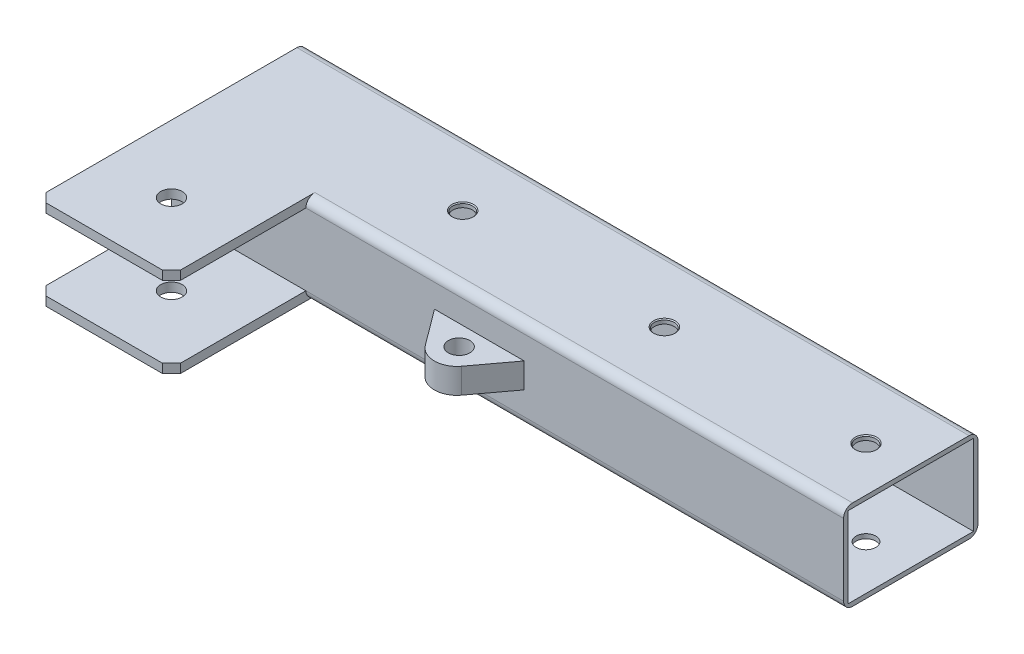
SolidWorks part; units mm, degrees
ref_plane "Front Plane" through (0, 0, 0) normal (0, 0, 1) x (1, 0, 0)
ref_plane "Top Plane" through (0, 0, 0) normal (0, 1, 0) x (1, 0, 0)
ref_plane "Right Plane" through (0, 0, 0) normal (1, 0, 0) x (0, 0, -1)
sketch "Sketch1" plane through (0, 0, 0) normal (0, 1, 0) x (1, 0, 0)
  line L3 (-375, 75) -> (375, 75)
  line L4 (375, -75) -> (375, 75)
  line L5 (-375, -75) -> (375, 75) construction
  line L6 (-375, 75) -> (375, -75) construction
  line L8 (-225, -75) -> (375, -75)
  line L11 (-375, 75) -> (-375, -75)
  line L14 (-375, -75) -> (-375, -225)
  line L15 (-375, -225) -> (-225, -225)
  line L16 (-225, -75) -> (-225, -225)
  circle A1 centre (-300, -150) radius 12
  point P0 (0, 0)
  point P6 (-375, -150)
  point P13 (-300, -225)
  dimension "D3" = 150
  dimension "D6" = 24
  dimension "D1" = 750
  dimension "D2" = 150
  dimension "D4" = 150
  dimension "D5" = 150
extrude "Boss-Extrude1" add sketch "Sketch1" along normal blind 100
sketch "Sketch2" plane through (375, 0, 0) normal (1, 0, 0) x (0, 0, -1)
  line L0 (-75, 100) -> (-75, 0) construction
  line L1 (-75, 100) -> (75, 100) construction
  line L2 (-70, 5) -> (70, 5)
  line L3 (75, 100) -> (75, 0) construction
  line L4 (-70, 5) -> (-70, 95)
  line L5 (-70, 95) -> (70, 95)
  line L6 (70, 5) -> (70, 95)
  line L7 (-70, 5) -> (70, 95) construction
  line L8 (-70, 95) -> (70, 5) construction
  point P0 (0, 50)
  point P4 (75, 50)
  dimension "D2" = 5
  dimension "D3" = 5
extrude "Cut-Extrude1" cut sketch "Sketch2" against normal through all contours L2 L6 L5 L4
sketch "Sketch3" plane through (0, 0, 0) normal (-1, 0, 0) x (0, 0, 1)
  line L5 (225, 100) -> (225, 0) construction
  line L6 (375, 10) -> (225, 10)
  line L7 (375, 10) -> (375, 90)
  line L12 (375, 90) -> (225, 90)
  line L14 (272.5, -25) -> (327.5, -25)
  line L15 (375, 10) -> (225, 90) construction
  line L16 (375, 90) -> (225, 10) construction
  line L17 (-75, 100) -> (-75, 0) construction
  line L19 (272.5, 125) -> (327.5, 125)
  line L20 (327.5, -25) -> (327.5, 125)
  line L21 (272.5, -25) -> (327.5, 125) construction
  line L22 (272.5, 125) -> (327.5, -25) construction
  line L24 (225, 10) -> (75, 10)
  line L25 (225, 10) -> (225, 90)
  line L26 (225, 90) -> (75, 90)
  line L27 (75, 90) -> (75, 10)
  point P0 (300, 50)
  point P10 (-75, 50)
  point P11 (300, 50)
  dimension "D1" = 80
  dimension "D2" = 150
  dimension "D3" = 55
  dimension "D4" = 150
extrude "Cut-Extrude2" cut sketch "Sketch3" along normal up to next contours L27 L26 L25 L24 | L14 L20 L19
fillet "Fillet2" radius 10 2 edges at (0, 0, -75) (0, 100, -75)
fillet "Fillet4" radius 10 2 edges at (75, 100, 75) (75, 0, 75)
chamfer "Chamfer1" distance 10 angle 45 4 edges at (-225, 5, 225) (-375, 5, 225) (-375, 95, 225) (-225, 95, 225)
hole_wizard "M24x2.0 Tapped Hole1" positions "Sketch6" profile "Sketch5" tap size "M24x2.0" standard "ANSI Metric" end condition through all
sketch "Sketch6" plane through (0, 100, 0) normal (0, 1, 0) x (1, 0, 0)
  line L0 (375, -65) -> (375, 65) construction
  line L1 (375, -75) -> (-225, -75) construction
  point P0 (100, 0)
  point P2 (325, 0)
  point P4 (-125, 0)
  dimension "D1" = 500
  dimension "D2" = 225
  dimension "D3" = 50
  dimension "D4" = 75
sketch "Sketch5" plane through (100, 100, 0) normal (1, 0, 0) x (0, 0, 1)
  line L0 (0, 0) -> (0, 100)
  line L1 (0, 100) -> (11, 100)
  line L2 (11, 100) -> (11, 1.025)
  line L3 (11, 1.025) -> (12.025, 0)
  line L5 (12.025, 0) -> (0, 0)
  line L6 (-11, 1.025) -> (-12.025, 0) construction
  line L11 (0, -6.35) -> (0, 107.95) construction
  dimension "Thru Tap Drill Dia." = 22
  dimension "Thru Tap Drill Depth" = 100
  dimension "Near C'Sink Dia." = 24.05
  dimension "Near C'Sink Angle" = 90
cosmetic thread "Hole Thread1" parameters "D2"=24
cosmetic thread "Hole Thread2" parameters "D2"=24
cosmetic thread "Hole Thread3" parameters "D2"=24
sketch "Sketch7" plane through (0, 100, 0) normal (0, 1, 0) x (1, 0, 0)
  line L0 (-81.4569, -75) -> (-51.7179, -115)
  line L1 (375, -75) -> (-225, -75) construction
  line L3 (-11.1959, -115) -> (18.5431, -75)
  line L4 (-81.4569, -75) -> (18.5431, -75)
  arc A0 (-27.508, -75) -> (-35.4058, -75) centre (-31.4569, -99.9364) ccw
  circle A1 centre (-31.4569, -97.5334) radius 12
  arc A2 (-51.7179, -115) -> (-11.1959, -115) centre (-31.4569, -99.9364) ccw
  dimension "D5" = 24
  dimension "D1" = 100
extrude "Boss-Extrude3" add sketch "Sketch7" against normal blind 28 from offset 36 contours L0 A2 L3 L4 A1
